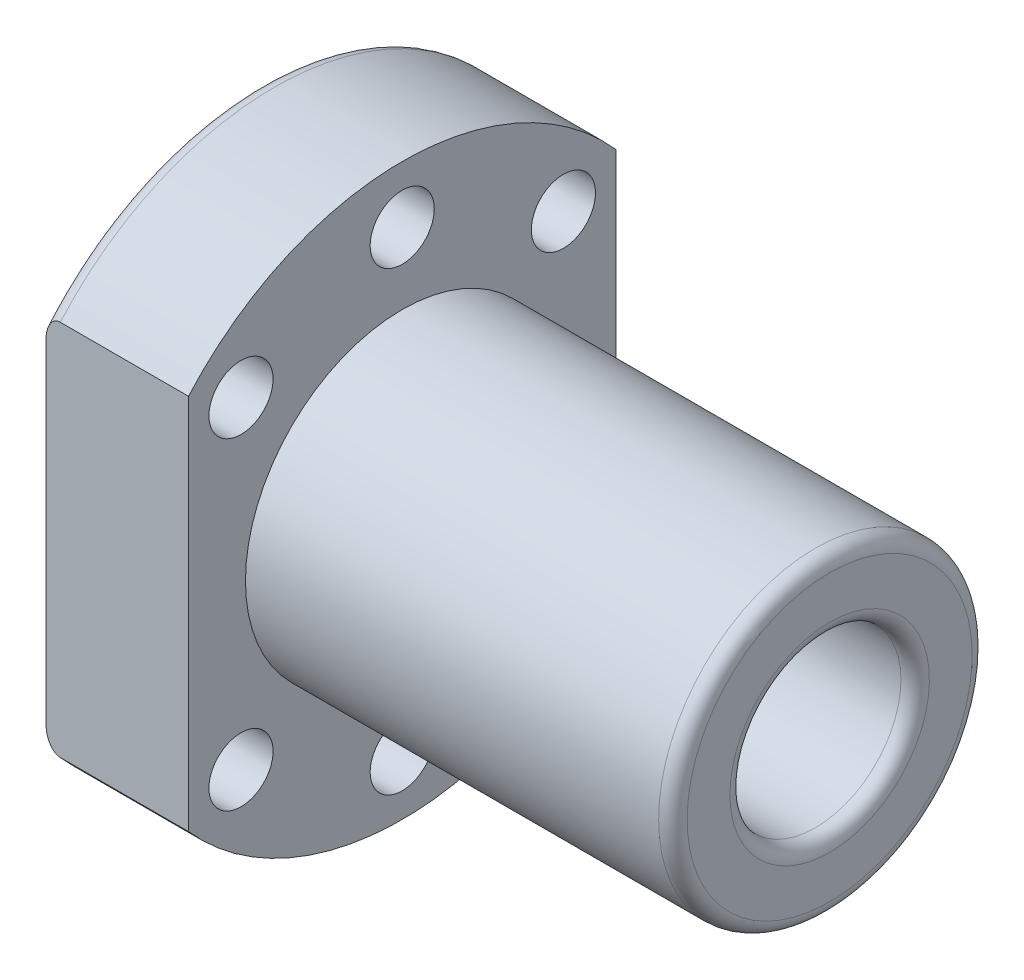
SolidWorks part; units mm, degrees
material "45 钢"
ref_plane "前视基准面" through (0, 0, 0) normal (0, 0, 1) x (1, 0, 0)
ref_plane "上视基准面" through (0, 0, 0) normal (0, 1, 0) x (1, 0, 0)
ref_plane "右视基准面" through (0, 0, 0) normal (1, 0, 0) x (0, 0, -1)
sketch "草图1" plane through (0, 0, 0) normal (0, 0, 1) x (1, 0, 0)
  line L0 (0, 0) -> (0, 20)
  line L1 (0, 20) -> (10, 20)
  line L2 (10, 20) -> (10, 11)
  line L3 (10, 11) -> (40, 11)
  line L4 (40, 11) -> (40, 0)
  line L5 (40, 0) -> (0, 0) construction
  line L6 (0, 0) -> (40, 0)
  dimension "D1" = 40
  dimension "D2" = 10
  dimension "D3" = 40
  dimension "D4" = 22
revolve "旋转1" add sketch "草图1" angle 360 about L5
sketch "草图2" plane through (0, 0, 0) normal (-1, 0, 0) x (0, 0, 1)
  circle A0 centre (0, 0) radius 6
  dimension "D1" = 12
extrude "切除-拉伸1" cut sketch "草图2" against normal through all
sketch "草图3" plane through (0, 0, 0) normal (-1, 0, 0) x (0, 0, 1)
  line L0 (-11.3137, 11.3137) -> (0, 0) construction
  line L1 (0, 0) -> (0, 16) construction
  circle A0 centre (0, 0) radius 16 construction
  circle A1 centre (0, 16) radius 2.25
  circle A2 centre (11.3137, 11.3137) radius 2.25
  circle A3 centre (16, 0) radius 2.25 construction
  circle A4 centre (11.3137, -11.3137) radius 2.25
  circle A5 centre (0, -16) radius 2.25
  circle A6 centre (-11.3137, -11.3137) radius 2.25
  circle A7 centre (-16, 0) radius 2.25 construction
  circle A8 centre (-11.3137, 11.3137) radius 2.25
  point P21 (0, 0)
  dimension "D1" = 32
  dimension "D2" = 4.5
  dimension "D3" = 8
extrude "切除-拉伸2" cut sketch "草图3" against normal through all
sketch "草图4" plane through (0, 0, 0) normal (-1, 0, 0) x (0, 0, 1)
  line L1 (-15, 25.4143) -> (15, 25.4143)
  line L2 (-15, 25.4143) -> (-15, -25.4143)
  line L3 (-15, -25.4143) -> (15, -25.4143)
  line L4 (15, 25.4143) -> (15, -25.4143)
  line L5 (-15, 25.4143) -> (15, -25.4143) construction
  line L6 (-15, -25.4143) -> (15, 25.4143) construction
  point P0 (0, 0)
  dimension "D1" = 30
extrude "切除-拉伸3" cut sketch "草图4" against normal blind 10 flip side to cut
fillet "圆角1" radius 1 5 edges at (40, 11, 0) (40, -6, 0) (0, -6, 0) (0, -20, 0) (0, 20, 0)
